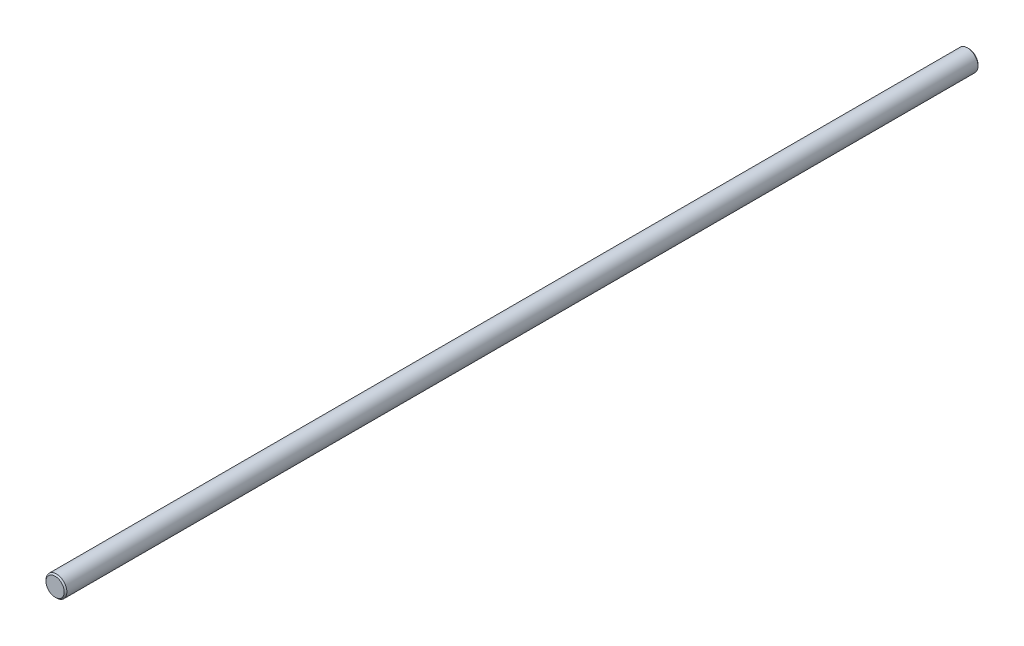
SolidWorks part; units mm, degrees
ref_plane "Plan de face" through (0, 0, 0) normal (0, 0, 1) x (1, 0, 0)
ref_plane "Plan de dessus" through (0, 0, 0) normal (0, 1, 0) x (1, 0, 0)
ref_plane "Plan de droite" through (0, 0, 0) normal (1, 0, 0) x (0, 0, -1)
sketch "Esquisse1" plane through (0, 0, 0) normal (0, 0, 1) x (1, 0, 0)
  circle A0 centre (0, 0) radius 4
  dimension "D1" = 8
extrude "Boss.-Extru.1" add sketch "Esquisse1" along normal mid plane 350
chamfer "Chanfrein1" distance 0.5 angle 45 2 edges at (4, 0, -175) (4, 0, 175)
